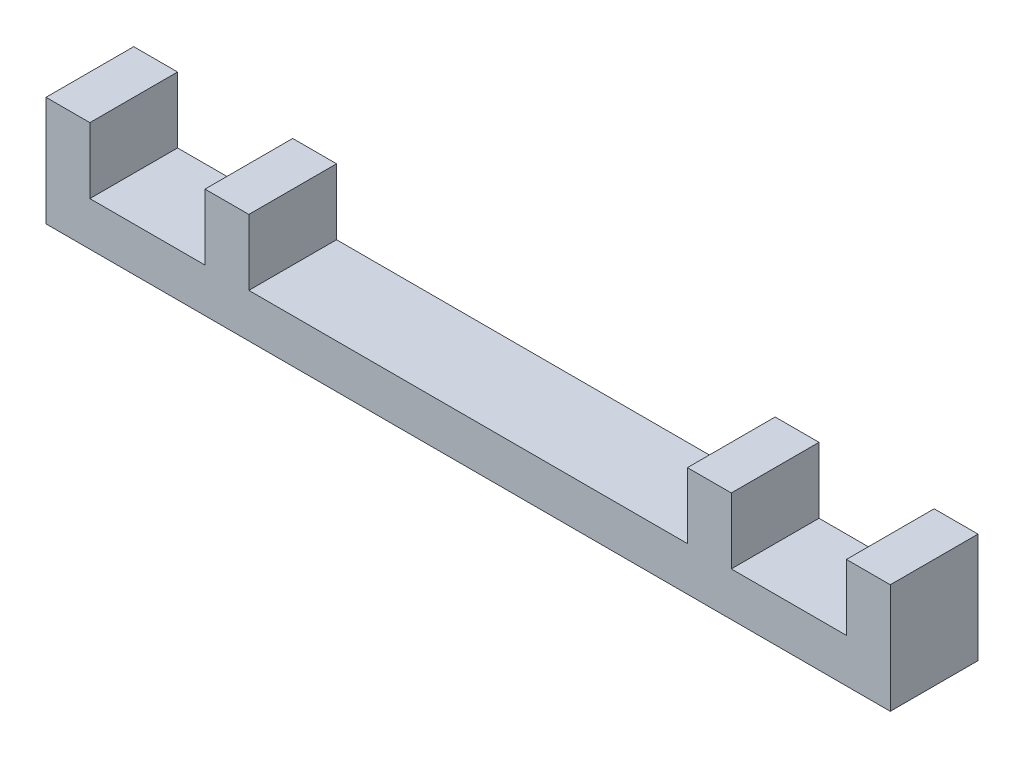
SolidWorks part; units mm, degrees
ref_plane "Front Plane" through (0, 0, 0) normal (0, 0, 1) x (1, 0, 0)
ref_plane "Top Plane" through (0, 0, 0) normal (0, 1, 0) x (1, 0, 0)
ref_plane "Right Plane" through (0, 0, 0) normal (1, 0, 0) x (0, 0, -1)
sketch "Sketch1" plane through (0, 0, 0) normal (0, 0, 1) x (1, 0, 0)
  line L5 (0, 0) -> (-20, 0)
  line L6 (-20, 0) -> (-20, 6)
  line L7 (-20, 6) -> (-24, 6)
  line L8 (-24, 6) -> (-24, 0)
  line L9 (-24, 0) -> (-34.5, 0)
  line L10 (-34.5, 0) -> (-34.5, 6)
  line L11 (-34.5, 6) -> (-38.5, 6)
  line L12 (-38.5, 6) -> (-38.5, -4)
  line L13 (-38.5, -4) -> (0, -4)
  line L14 (0, -4) -> (0, 0)
  point P1 (-34.5, 3)
  dimension "D1" = 20
  dimension "D2" = 24
  dimension "D3" = 34.5
  dimension "D4" = 38.5
  dimension "D5" = 10
  dimension "D6" = 6
extrude "Boss-Extrude2" add sketch "Sketch1" along normal blind 8
mirror "Mirror1" about plane through (0, 0, 0) normal (1, 0, 0) of bodies 102
